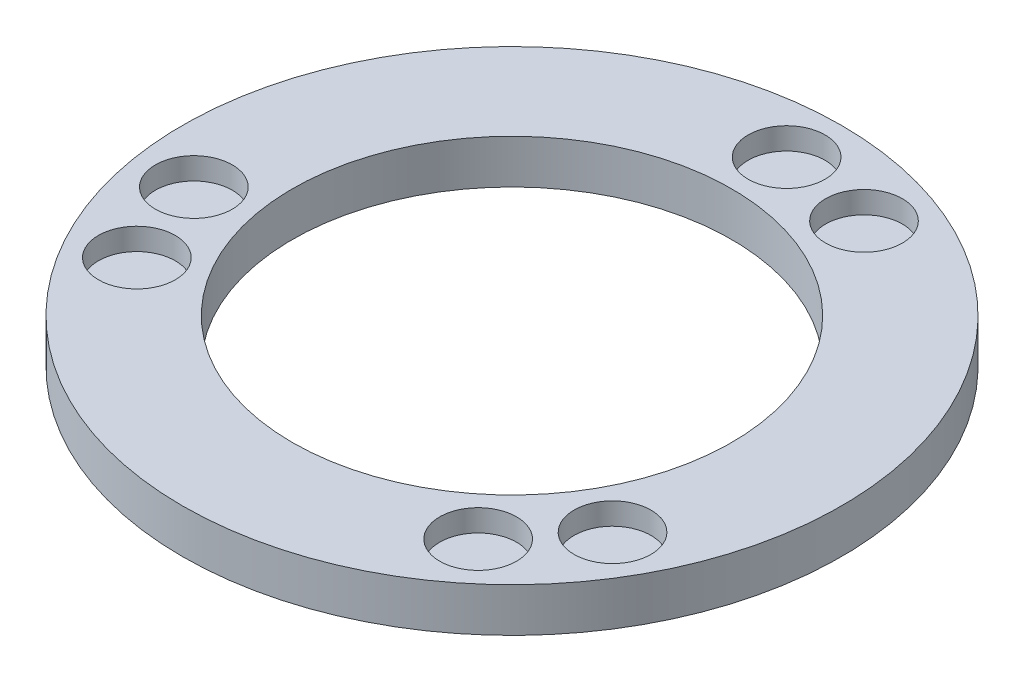
SolidWorks part; units mm, degrees
material "6061 Alloy"
ref_plane "Front" through (0, 0, 0) normal (0, 0, 1) x (1, 0, 0)
ref_plane "Top" through (0, 0, 0) normal (0, 1, 0) x (1, 0, 0)
ref_plane "Right" through (0, 0, 0) normal (1, 0, 0) x (0, 0, -1)
sketch "Sketch1" plane through (0, 0, 0) normal (0, 1, 0) x (1, 0, 0)
  circle A0 centre (0, 0) radius 150
  circle A1 centre (0, 0) radius 100
  dimension "D1" = 50
extrude "Extrude1" add sketch "Sketch1" against normal blind 20
sketch "Sketch2" plane through (0, 0, 0) normal (0, 1, 0) x (1, 0, 0)
  line L1 (0, 0) -> (42.7525, 117.4616) construction
  line L2 (0, -11) -> (0, 11) construction
  circle A0 centre (0, 0) radius 125 construction
  circle A1 centre (0, 125) radius 17.5
  circle A2 centre (42.7525, 117.4616) radius 17.5
  circle A3 centre (108.2532, -62.5) radius 17.5
  circle A4 centre (80.3485, -95.7556) radius 17.5
  circle A5 centre (-108.2532, -62.5) radius 17.5
  circle A6 centre (-123.101, -21.706) radius 17.5
  dimension "D1" = 20
extrude "Cut-Extrude1" cut sketch "Sketch2" against normal blind 10
